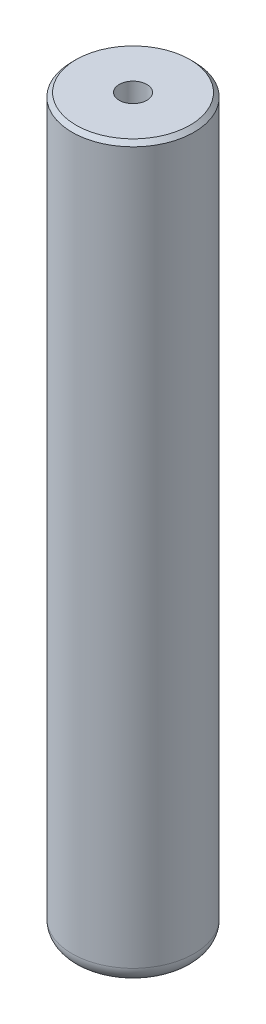
SolidWorks part; units mm, degrees
material "6061-T6 Aluminum"
ref_plane "Front Plane" through (0, 0, 0) normal (0, 0, 1) x (1, 0, 0)
ref_plane "Top Plane" through (0, 0, 0) normal (0, 1, 0) x (1, 0, 0)
ref_plane "Right Plane" through (0, 0, 0) normal (1, 0, 0) x (0, 0, -1)
sketch "Sketch1" plane through (0, 0, 0) normal (0, 1, 0) x (1, 0, 0)
  circle A0 centre (0, 0) radius 15
  dimension "D1" = 30
extrude "Boss-Extrude1" add sketch "Sketch1" along normal blind 180
fillet "Fillet1" radius 4 1 edges at (0, 0, 15)
chamfer "Chamfer1" distance 1 angle 45 1 edges at (0, 180, 15)
sketch "Sketch2" plane through (0, 180, 0) normal (0, 1, 0) x (1, 0, 0)
  point P0 (0, 0)
hole_wizard "M8x1.25 Tapped Hole1" positions "Sketch2" profile "Sketch3" tap size "M8x1.25" standard "ANSI Metric"
sketch "Sketch3" plane through (0, 180, 0) normal (1, 0, 0) x (0, 0, 1)
  line L0 (0, 0) -> (0, 21.7929)
  line L1 (0, 21.7929) -> (3.4, 19.75)
  line L2 (3.4, 19.75) -> (3.4, 0)
  line L5 (3.4, 0) -> (0, 0)
  line L10 (0, 21.7929) -> (-3.4, 19.75) construction
  line L11 (0, -6.35) -> (0, 107.95) construction
  dimension "Tap Drill Dia." = 6.8
  dimension "Tap Drill Depth" = 19.75
  dimension "Drill Angle" = 118
cosmetic thread "Hole Thread1" parameters "D1"=16, "D2"=8
